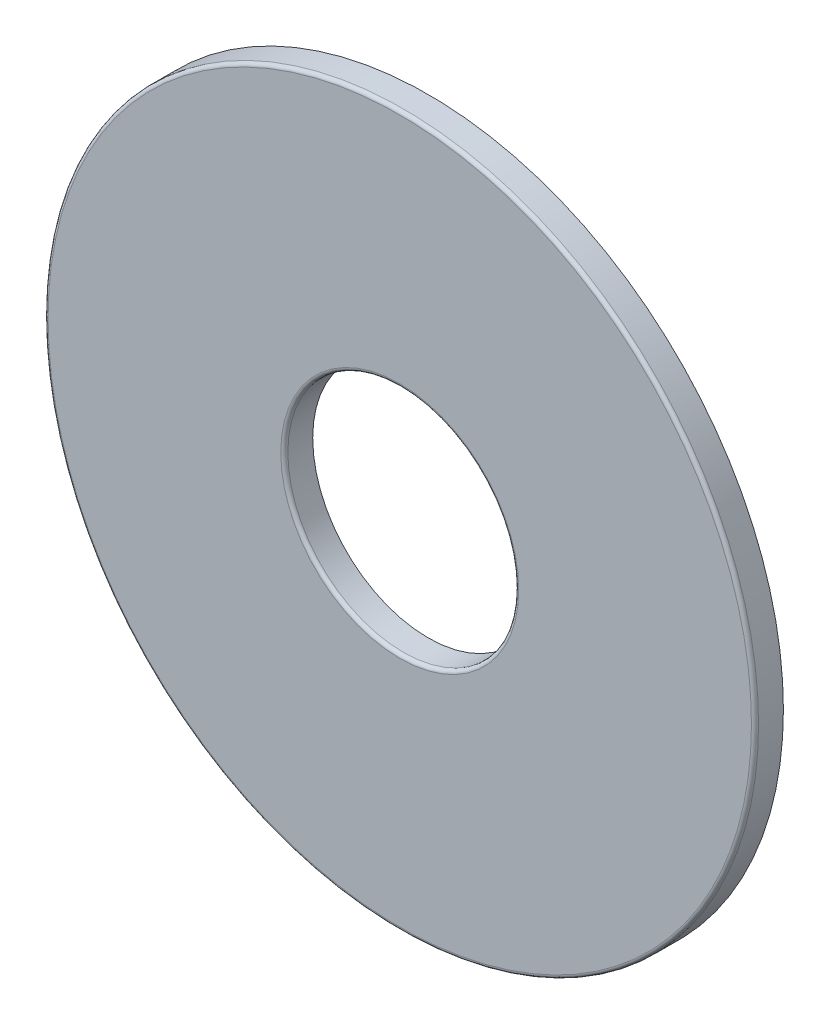
SolidWorks part; units mm, degrees
ref_plane "Front Plane" through (0, 0, 0) normal (0, 0, 1) x (1, 0, 0)
ref_plane "Top Plane" through (0, 0, 0) normal (0, 1, 0) x (1, 0, 0)
ref_plane "Right Plane" through (0, 0, 0) normal (1, 0, 0) x (0, 0, -1)
sketch "Sketch1" plane through (0, 0, 0) normal (0, 0, 1) x (1, 0, 0)
  circle A0 centre (0, 0) radius 3.25
  circle A1 centre (0, 0) radius 10
  dimension "D1" = 6.5
  dimension "D2" = 20
extrude "Boss-Extrude1" add sketch "Sketch1" along normal blind 0.8
fillet "Fillet1" radius 0.1 2 edges at (10, 0, 0.8) (3.25, 0, 0.8)
